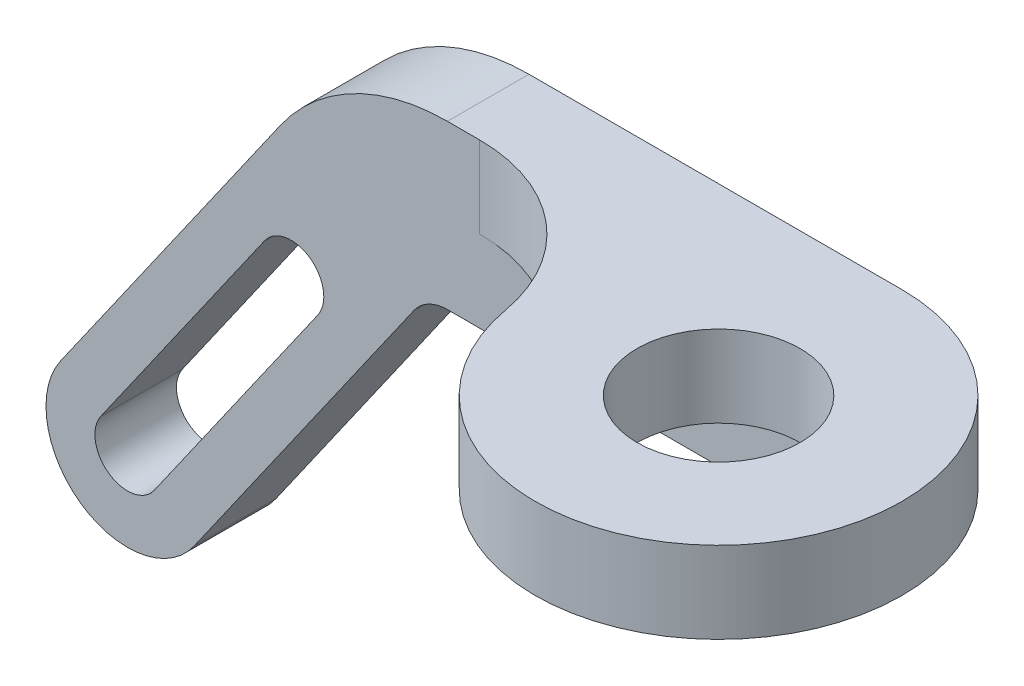
SolidWorks part; units mm, degrees
ref_plane "Front Plane" through (0, 0, 0) normal (0, 0, 1) x (1, 0, 0)
ref_plane "Top Plane" through (0, 0, 0) normal (0, 1, 0) x (1, 0, 0)
ref_plane "Right Plane" through (0, 0, 0) normal (1, 0, 0) x (0, 0, -1)
sketch "Sketch1" plane through (0, 0, 0) normal (0, 0, 1) x (1, 0, 0)
  line L0 (-47.4288, -24.1491) -> (-20.4788, 14.3394)
  line L1 (0, 25) -> (45.7628, 25)
  line L2 (-31.0457, -35.6207) -> (-4.0958, 2.8679)
  line L3 (0, 5) -> (45.7628, 5)
  line L4 (45.7628, 25) -> (45.7628, 5)
  arc A0 (-20.4788, 14.3394) -> (0, 25) centre (0, 0) cw
  arc A1 (-4.0958, 2.8679) -> (0, 5) centre (0, 0) cw
  arc A2 (-47.4288, -24.1491) -> (-31.0457, -35.6207) centre (-39.2372, -29.8849) ccw
  arc A3 (-20.4788, 14.3394) -> (0, 25) centre (0, 0) cw construction
  point P2 (-13.0142, 25)
  dimension "D3" = 25
  dimension "D1" = 125
  dimension "D4" = 60
  dimension "D5" = 85
  dimension "D2" = 20
extrude "Boss-Extrude1" add sketch "Sketch1" along normal blind 10
sketch "Sketch2" plane through (0, 25, 0) normal (0, 1, 0) x (1, 0, 0)
  line L0 (45.7628, 0) -> (0, 0) construction
  line L1 (45.7628, -10) -> (45.7628, 0) construction
  circle A0 centre (45.7628, -22.5) radius 22.5
  dimension "D1" = 45
extrude "Boss-Extrude2" add sketch "Sketch2" against normal blind 10
fillet "Fillet1" radius 20 1 edges at (27.0545, 20, 10)
sketch "Sketch3" plane through (0, 0, 10) normal (0, 0, 1) x (1, 0, 0)
  line L0 (-39.2372, -29.8849) -> (-19.1621, -1.2146) construction
  line L1 (-42.5139, -27.5906) -> (-22.4387, 1.0797)
  line L2 (-35.9606, -32.1792) -> (-15.8855, -3.5089)
  line L3 (-31.0457, -35.6207) -> (-4.0958, 2.8679) construction
  arc A0 (-42.5139, -27.5906) -> (-35.9606, -32.1792) centre (-39.2372, -29.8849) ccw
  arc A1 (-15.8855, -3.5089) -> (-22.4387, 1.0797) centre (-19.1621, -1.2146) ccw
  point P3 (-29.1997, -15.5497)
  dimension "D1" = 8
  dimension "D2" = 43
extrude "Cut-Extrude1" cut sketch "Sketch3" against normal through all
hole_wizard "Ø20.0 (20) Diameter Hole1" positions "Sketch5" profile "Sketch4" hole size "Ø20.0" standard "ANSI Metric" end condition through all
sketch "Sketch5" plane through (0, 25, 0) normal (0, 1, 0) x (1, 0, 0)
  point P0 (45.7628, -22.5)
sketch "Sketch4" plane through (45.7628, 25, 22.5) normal (1, 0, 0) x (0, 0, 1)
  line L0 (0, 0) -> (0, 64.8849)
  line L1 (0, 64.8849) -> (10, 64.8849)
  line L2 (10, 64.8849) -> (10, 0)
  line L5 (10, 0) -> (0, 0)
  line L11 (0, -6.35) -> (0, 107.95) construction
  dimension "Thru Hole Dia." = 20
  dimension "Thru Hole Depth" = 64.8849
